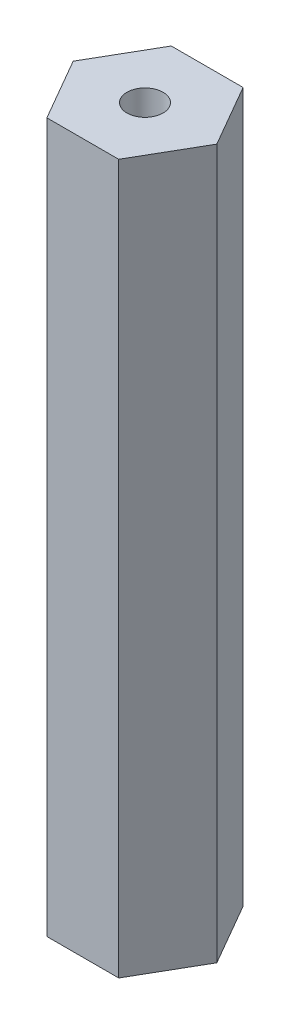
SolidWorks part; units mm, degrees
ref_plane "前视基准面" through (0, 0, 0) normal (0, 0, 1) x (1, 0, 0)
ref_plane "上视基准面" through (0, 0, 0) normal (0, 1, 0) x (1, 0, 0)
ref_plane "右视基准面" through (0, 0, 0) normal (1, 0, 0) x (0, 0, -1)
other "Configuration Table"
sketch "草图1" plane through (0, 0, 0) normal (0, 1, 0) x (1, 0, 0)
  line L1 (5.7735, 0) -> (2.8868, 5)
  line L2 (2.8868, 5) -> (-2.8868, 5)
  line L3 (-2.8868, 5) -> (-5.7735, 0)
  line L4 (-5.7735, 0) -> (-2.8868, -5)
  line L5 (-2.8868, -5) -> (2.8868, -5)
  line L6 (2.8868, -5) -> (5.7735, 0)
  circle A0 centre (0, 0) radius 5 construction
  circle A1 centre (0, 0) radius 1.45
  dimension "D2" = 2.9
  dimension "D1" = 10
extrude "凸台-拉伸1" add sketch "草图1" along normal blind 57
